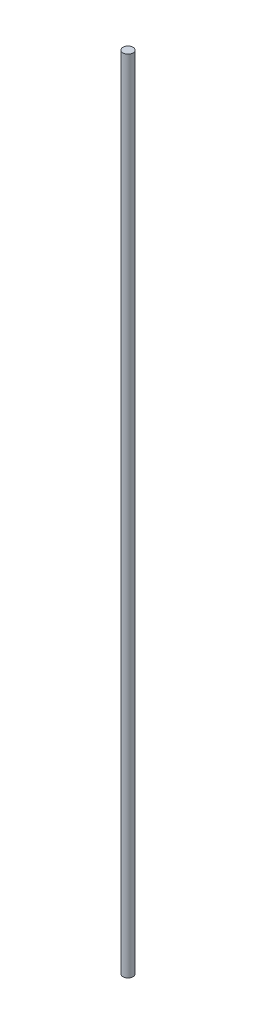
SolidWorks part; units mm, degrees
ref_plane "Front Plane" through (0, 0, 0) normal (0, 0, 1) x (1, 0, 0)
ref_plane "Top Plane" through (0, 0, 0) normal (0, 1, 0) x (1, 0, 0)
ref_plane "Right Plane" through (0, 0, 0) normal (1, 0, 0) x (0, 0, -1)
sketch "Sketch1" plane through (0, 0, 0) normal (0, 1, 0) x (1, 0, 0)
  circle A0 centre (0, 0) radius 1.27
extrude "Boss-Extrude1" add sketch "Sketch1" along normal blind 203.2
